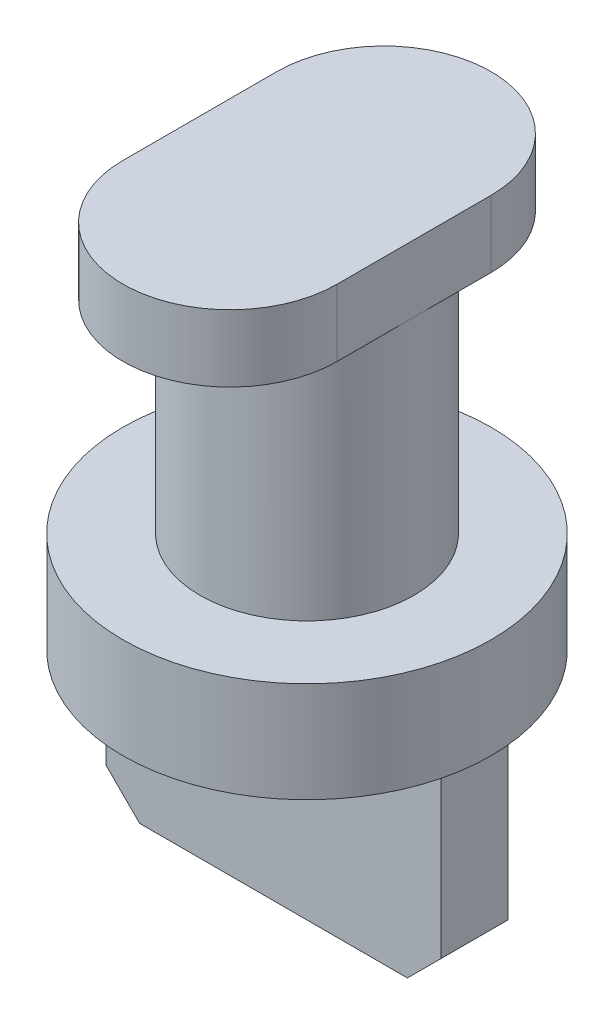
SolidWorks part; units mm, degrees
ref_plane "正面" through (0, 0, 0) normal (0, 0, 1) x (1, 0, 0)
ref_plane "平面" through (0, 0, 0) normal (0, 1, 0) x (1, 0, 0)
ref_plane "右側面" through (0, 0, 0) normal (1, 0, 0) x (0, 0, -1)
sketch "ｽｹｯﾁ2" plane through (0, 0, 0) normal (0, 0, 1) x (1, 0, 0)
  line L1 (-2, 0) -> (2, 0)
  line L2 (-2.5, 0.5) -> (-2.5, 3)
  line L3 (-2.5, 3) -> (2.5, 3)
  line L4 (2.5, 0.5) -> (2.5, 3)
  line L5 (2, 0) -> (2.5, 0.5)
  line L6 (-2.5, 0.5) -> (-2, 0)
  point P3 (2.5, 0)
  point P6 (-2.5, 0)
  point P9 (0, 0)
  dimension "D1" = 5
  dimension "D2" = 3
extrude "ﾎﾞｽ - 押し出し1" add sketch "ｽｹｯﾁ2" along normal mid plane 1
sketch "ｽｹｯﾁ3" plane through (0, 3, 0) normal (0, 1, 0) x (1, 0, 0)
  line L0 (-2.5, 0) -> (2.5, 0) construction
  line L1 (2.5, -0.5) -> (2.5, 0.5) construction
  line L2 (0, 0.5) -> (0, -0.5) construction
  line L3 (2.5, 0.5) -> (-2.5, 0.5) construction
  line L4 (2.5, -0.5) -> (-2.5, -0.5) construction
  line L5 (-2.5, -0.5) -> (-2.5, 0.5) construction
  circle A0 centre (0, 0) radius 2.75
  dimension "D1" = 5.5
extrude "ﾎﾞｽ - 押し出し2" add sketch "ｽｹｯﾁ3" along normal blind 1.5
sketch "ｽｹｯﾁ5" plane through (0, 4.5, 0) normal (0, 1, 0) x (1, 0, 0)
  circle A0 centre (0, 0) radius 1.6
  dimension "D1" = 3.2
extrude "ﾎﾞｽ - 押し出し3" add sketch "ｽｹｯﾁ5" along normal blind 3.6
sketch "ｽｹｯﾁ6" plane through (0, 8.1, 0) normal (0, 1, 0) x (1, 0, 0)
  line L0 (0, -1.15) -> (0, 1.15) construction
  line L1 (-1.6, -1.15) -> (-1.6, 1.15)
  line L2 (1.6, -1.15) -> (1.6, 1.15)
  arc A0 (-1.6, -1.15) -> (1.6, -1.15) centre (0, -1.15) ccw
  arc A1 (1.6, 1.15) -> (-1.6, 1.15) centre (0, 1.15) ccw
  point P2 (0, 0)
  dimension "D2" = 1.6
  dimension "D1" = 2.3
extrude "ﾎﾞｽ - 押し出し4" add sketch "ｽｹｯﾁ6" along normal blind 1
